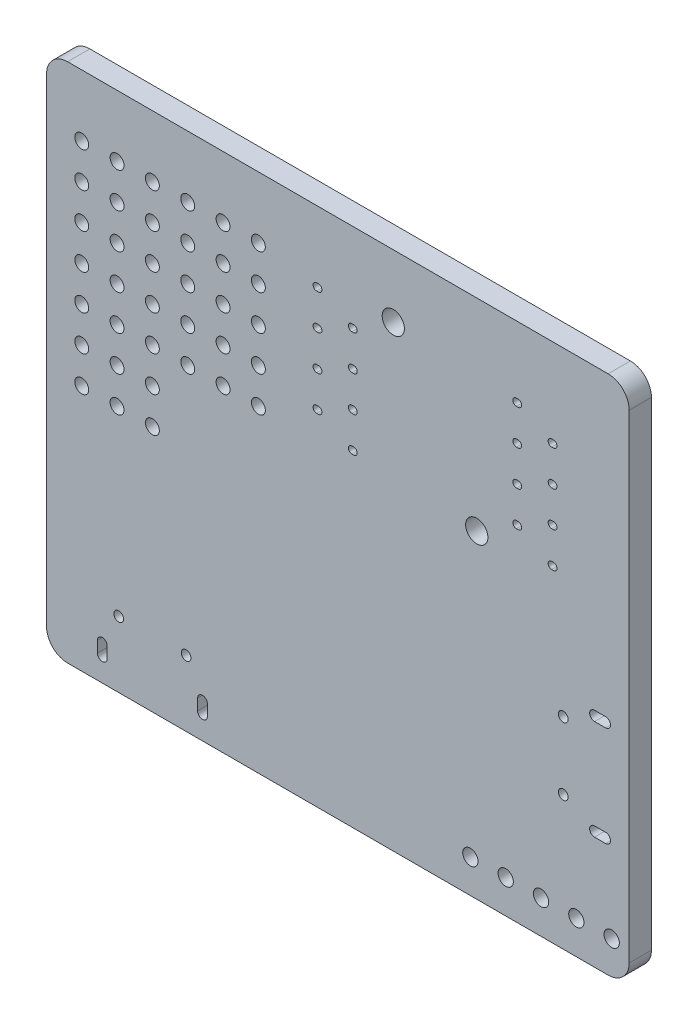
SolidWorks part; units mm, degrees
ref_plane "Front" through (0, 0, 0) normal (0, 0, 1) x (1, 0, 0)
ref_plane "Top" through (0, 0, 0) normal (0, 1, 0) x (1, 0, 0)
ref_plane "Right" through (0, 0, 0) normal (1, 0, 0) x (0, 0, -1)
ref_plane "Plane1" through (0, 0, 0) normal (0, 0, -1) x (-1, 0, 0)
sketch "Sketch1" plane through (0, 0, 0) normal (0, 0, -1) x (-1, 0, 0)
  line L0 (-19.5535, 32.6391) -> (-19.4265, 32.6391)
  line L1 (-19.4265, 32.1311) -> (-19.5535, 32.1311)
  line L2 (-19.5535, 30.0991) -> (-19.4265, 30.0991)
  line L3 (-19.4265, 29.5911) -> (-19.5535, 29.5911)
  line L4 (-19.5535, 27.5591) -> (-19.4265, 27.5591)
  line L5 (-19.4265, 27.0511) -> (-19.5535, 27.0511)
  line L6 (-19.5535, 25.0191) -> (-19.4265, 25.0191)
  line L7 (-19.4265, 24.511) -> (-19.5535, 24.511)
  line L8 (-22.0935, 31.3691) -> (-21.9665, 31.3691)
  line L9 (-21.9665, 30.8611) -> (-22.0935, 30.8611)
  line L10 (-22.0935, 28.8291) -> (-21.9665, 28.8291)
  line L11 (-21.9665, 28.3211) -> (-22.0935, 28.3211)
  line L12 (-22.0935, 26.2891) -> (-21.9665, 26.2891)
  line L13 (-21.9665, 25.7811) -> (-22.0935, 25.7811)
  line L14 (-33.9136, 32.6391) -> (-33.7866, 32.6391)
  line L15 (-33.7866, 32.1311) -> (-33.9136, 32.1311)
  line L16 (-33.9136, 30.0991) -> (-33.7866, 30.0991)
  line L17 (-33.7866, 29.5911) -> (-33.9136, 29.5911)
  line L18 (-36.4536, 31.3691) -> (-36.3266, 31.3691)
  line L19 (-36.3266, 30.8611) -> (-36.4536, 30.8611)
  line L20 (-33.9136, 27.5591) -> (-33.7866, 27.5591)
  line L21 (-33.7866, 27.0511) -> (-33.9136, 27.0511)
  line L22 (-36.4536, 28.8291) -> (-36.3266, 28.8291)
  line L23 (-36.3266, 28.3211) -> (-36.4536, 28.3211)
  line L24 (-36.4536, 26.2891) -> (-36.3266, 26.2891)
  line L25 (-36.3266, 25.7811) -> (-36.4536, 25.7811)
  line L26 (-22.0935, 23.749) -> (-21.9665, 23.749)
  line L27 (-21.9665, 23.241) -> (-22.0935, 23.241)
  line L28 (-33.9136, 25.0191) -> (-33.7866, 25.0191)
  line L29 (-33.7866, 24.511) -> (-33.9136, 24.511)
  line L30 (-36.4536, 23.749) -> (-36.3266, 23.749)
  line L31 (-36.3266, 23.241) -> (-36.4536, 23.241)
  line L32 (-3.6701, 2.504) -> (-3.6701, 1.7039)
  line L33 (-4.3701, 1.7039) -> (-4.3701, 2.504)
  line L34 (-10.8699, 2.504) -> (-10.8699, 1.7039)
  line L35 (-11.57, 1.7039) -> (-11.57, 2.504)
  line L36 (-40.2061, 16.015) -> (-39.406, 16.015)
  line L37 (-39.406, 15.3149) -> (-40.2061, 15.3149)
  line L38 (-40.2061, 8.8151) -> (-39.406, 8.8151)
  line L39 (-39.406, 8.1151) -> (-40.2061, 8.1151)
  line L40 (-40.3861, 0.0127) -> (-1.524, 0.0127)
  line L41 (-0.0127, 1.524) -> (-0.0127, 35.9411)
  line L42 (-1.524, 37.4524) -> (-40.3861, 37.4524)
  line L43 (-41.8974, 35.9411) -> (-41.8974, 1.524)
  circle A0 centre (-2.54, 33.0201) radius 0.5
  circle A1 centre (-5.08, 33.0201) radius 0.5
  circle A2 centre (-2.54, 30.4801) radius 0.5
  circle A3 centre (-5.08, 30.4801) radius 0.5
  circle A4 centre (-7.62, 33.0201) radius 0.5
  circle A5 centre (-10.16, 33.0201) radius 0.5
  circle A6 centre (-7.62, 30.4801) radius 0.5
  circle A7 centre (-10.16, 30.4801) radius 0.5
  circle A8 centre (-2.54, 27.9401) radius 0.5
  circle A9 centre (-5.08, 27.9401) radius 0.5
  circle A10 centre (-7.62, 27.9401) radius 0.5
  circle A11 centre (-10.16, 27.9401) radius 0.5
  circle A12 centre (-12.7, 33.0201) radius 0.5
  circle A13 centre (-15.24, 33.0201) radius 0.5
  circle A14 centre (-12.7, 30.4801) radius 0.5
  circle A15 centre (-15.24, 30.4801) radius 0.5
  arc A16 (-19.5535, 32.1311) -> (-19.5535, 32.6391) centre (-19.5535, 32.3851) cw
  arc A17 (-19.4265, 32.6391) -> (-19.4265, 32.1311) centre (-19.4265, 32.3851) cw
  arc A18 (-19.5535, 29.5911) -> (-19.5535, 30.0991) centre (-19.5535, 29.8451) cw
  arc A19 (-19.4265, 30.0991) -> (-19.4265, 29.5911) centre (-19.4265, 29.8451) cw
  circle A20 centre (-12.7, 27.9401) radius 0.5
  circle A21 centre (-15.24, 27.9401) radius 0.5
  arc A22 (-19.5535, 27.0511) -> (-19.5535, 27.5591) centre (-19.5535, 27.3051) cw
  arc A23 (-19.4265, 27.5591) -> (-19.4265, 27.0511) centre (-19.4265, 27.3051) cw
  circle A24 centre (-2.54, 25.4001) radius 0.5
  circle A25 centre (-5.08, 25.4001) radius 0.5
  circle A26 centre (-2.54, 22.86) radius 0.5
  circle A27 centre (-5.08, 22.86) radius 0.5
  circle A28 centre (-7.62, 25.4001) radius 0.5
  circle A29 centre (-10.16, 25.4001) radius 0.5
  circle A30 centre (-7.62, 22.86) radius 0.5
  circle A31 centre (-10.16, 22.86) radius 0.5
  circle A32 centre (-2.54, 20.32) radius 0.5
  circle A33 centre (-5.08, 20.32) radius 0.5
  circle A34 centre (-2.54, 17.78) radius 0.5
  circle A35 centre (-5.08, 17.78) radius 0.5
  circle A36 centre (-7.62, 20.32) radius 0.5
  circle A37 centre (-7.62, 17.78) radius 0.5
  circle A38 centre (-12.7, 25.4001) radius 0.5
  circle A39 centre (-15.24, 25.4001) radius 0.5
  circle A40 centre (-12.7, 22.86) radius 0.5
  circle A41 centre (-15.24, 22.86) radius 0.5
  arc A42 (-19.5535, 24.511) -> (-19.5535, 25.0191) centre (-19.5535, 24.765) cw
  arc A43 (-19.4265, 25.0191) -> (-19.4265, 24.511) centre (-19.4265, 24.765) cw
  circle A44 centre (-24.9401, 32.9401) radius 0.8
  arc A45 (-22.0935, 30.8611) -> (-22.0935, 31.3691) centre (-22.0935, 31.1151) cw
  arc A46 (-21.9665, 31.3691) -> (-21.9665, 30.8611) centre (-21.9665, 31.1151) cw
  arc A47 (-22.0935, 28.3211) -> (-22.0935, 28.8291) centre (-22.0935, 28.5751) cw
  arc A48 (-21.9665, 28.8291) -> (-21.9665, 28.3211) centre (-21.9665, 28.5751) cw
  arc A49 (-22.0935, 25.7811) -> (-22.0935, 26.2891) centre (-22.0935, 26.0351) cw
  arc A50 (-21.9665, 26.2891) -> (-21.9665, 25.7811) centre (-21.9665, 26.0351) cw
  arc A51 (-33.9136, 32.1311) -> (-33.9136, 32.6391) centre (-33.9136, 32.3851) cw
  arc A52 (-33.7866, 32.6391) -> (-33.7866, 32.1311) centre (-33.7866, 32.3851) cw
  arc A53 (-33.9136, 29.5911) -> (-33.9136, 30.0991) centre (-33.9136, 29.8451) cw
  arc A54 (-33.7866, 30.0991) -> (-33.7866, 29.5911) centre (-33.7866, 29.8451) cw
  arc A55 (-36.4536, 30.8611) -> (-36.4536, 31.3691) centre (-36.4536, 31.1151) cw
  arc A56 (-36.3266, 31.3691) -> (-36.3266, 30.8611) centre (-36.3266, 31.1151) cw
  arc A57 (-33.9136, 27.0511) -> (-33.9136, 27.5591) centre (-33.9136, 27.3051) cw
  arc A58 (-33.7866, 27.5591) -> (-33.7866, 27.0511) centre (-33.7866, 27.3051) cw
  arc A59 (-36.4536, 28.3211) -> (-36.4536, 28.8291) centre (-36.4536, 28.5751) cw
  arc A60 (-36.3266, 28.8291) -> (-36.3266, 28.3211) centre (-36.3266, 28.5751) cw
  arc A61 (-36.4536, 25.7811) -> (-36.4536, 26.2891) centre (-36.4536, 26.0351) cw
  arc A62 (-36.3266, 26.2891) -> (-36.3266, 25.7811) centre (-36.3266, 26.0351) cw
  arc A63 (-22.0935, 23.241) -> (-22.0935, 23.749) centre (-22.0935, 23.495) cw
  arc A64 (-21.9665, 23.749) -> (-21.9665, 23.241) centre (-21.9665, 23.495) cw
  circle A65 centre (-30.9401, 22.94) radius 0.8
  arc A66 (-33.9136, 24.511) -> (-33.9136, 25.0191) centre (-33.9136, 24.765) cw
  arc A67 (-33.7866, 25.0191) -> (-33.7866, 24.511) centre (-33.7866, 24.765) cw
  arc A68 (-36.4536, 23.241) -> (-36.4536, 23.749) centre (-36.4536, 23.495) cw
  arc A69 (-36.3266, 23.749) -> (-36.3266, 23.241) centre (-36.3266, 23.495) cw
  circle A70 centre (-5.195, 4.754) radius 0.35
  arc A71 (-4.3701, 2.504) -> (-3.6701, 2.504) centre (-4.0201, 2.504) cw
  arc A72 (-3.6701, 1.7039) -> (-4.3701, 1.7039) centre (-4.0201, 1.7039) cw
  circle A73 centre (-10.045, 4.754) radius 0.35
  arc A74 (-11.57, 2.504) -> (-10.8699, 2.504) centre (-11.2199, 2.504) cw
  arc A75 (-10.8699, 1.7039) -> (-11.57, 1.7039) centre (-11.2199, 1.7039) cw
  arc A76 (-40.2061, 15.3149) -> (-40.2061, 16.015) centre (-40.2061, 15.6649) cw
  arc A77 (-39.406, 16.015) -> (-39.406, 15.3149) centre (-39.406, 15.6649) cw
  circle A78 centre (-37.1561, 14.49) radius 0.35
  circle A79 centre (-37.1561, 9.64) radius 0.35
  circle A80 centre (-30.4801, 2.413) radius 0.55
  arc A81 (-40.2061, 8.1151) -> (-40.2061, 8.8151) centre (-40.2061, 8.4651) cw
  arc A82 (-39.406, 8.8151) -> (-39.406, 8.1151) centre (-39.406, 8.4651) cw
  circle A83 centre (-33.0201, 2.413) radius 0.55
  circle A84 centre (-35.5601, 2.413) radius 0.55
  circle A85 centre (-38.1001, 2.413) radius 0.55
  circle A86 centre (-40.6401, 2.413) radius 0.55
  arc A87 (-41.8974, 1.524) -> (-40.3861, 0.0127) centre (-40.3861, 1.524) ccw
  arc A88 (-1.524, 0.0127) -> (-0.0127, 1.524) centre (-1.524, 1.524) ccw
  arc A89 (-0.0127, 35.9411) -> (-1.524, 37.4524) centre (-1.524, 35.9411) ccw
  arc A90 (-40.3861, 37.4524) -> (-41.8974, 35.9411) centre (-40.3861, 35.9411) ccw
extrude "Boss-Extrude1" add sketch "Sketch1" against normal blind 1.6001
ref_plane "Plane2" through (0, 18.7325, 0) normal (0, -1, 0) x (-1, 0, 0)
ref_plane "Plane3" through (20.955, 0, 0) normal (-1, 0, 0) x (0, 0, -1)
